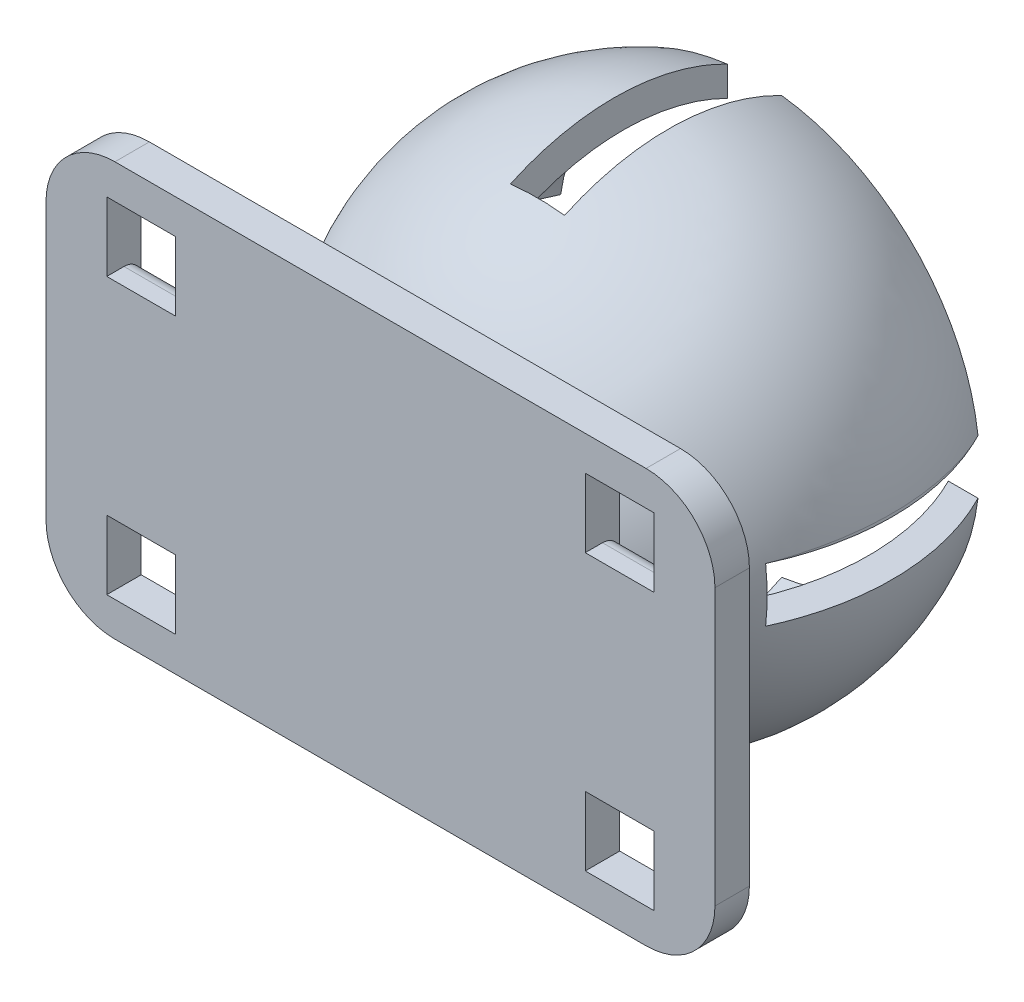
SolidWorks part; units mm, degrees
ref_plane "Front Plane" through (0, 0, 0) normal (0, 0, 1) x (1, 0, 0)
ref_plane "Top Plane" through (0, 0, 0) normal (0, 1, 0) x (1, 0, 0)
ref_plane "Right Plane" through (0, 0, 0) normal (1, 0, 0) x (0, 0, -1)
sketch "Sketch1" plane through (0, 0, 0) normal (0, 1, 0) x (1, 0, 0)
  line L0 (0, -22) -> (0, 22) construction
  line L1 (0, 22) -> (0, -22) construction
  line L3 (-16.302, 14.1421) -> (-19.0121, 14.1421) construction
  line L7 (0, -19.858) -> (0, -22)
  line L8 (-18.0365, 11.2951) -> (-20.7467, 11.2951)
  arc A4 (-19.0121, 14.1421) -> (0, -22) centre (-0.4092, 0.8563) ccw construction
  arc A6 (0, -19.858) -> (-20.0749, 4.7286) centre (1.3006, 1.6928) cw construction
  arc A9 (0, -19.858) -> (-18.0365, 11.2951) centre (1.3006, 1.6928) cw
  arc A10 (-20.7467, 11.2951) -> (0, -22) centre (-0.4092, 0.8563) ccw
  point P4 (0, 0)
  point P8 (0, 0)
  dimension "D1" = 44
  dimension "D2" = 21.59
  dimension "D3" = 22.86
  dimension "D4" = 36.1421
  dimension "D5" = 2.7102
  dimension "D6" = 21.59
revolve "Revolve2" add sketch "Sketch1" angle 360 about L0
sketch "Sketch2" plane through (0, 0, 0) normal (0, 1, 0) x (1, 0, 0)
  line L7 (20.7467, 11.2951) -> (-20.7467, 11.2951) construction
  line L16 (2.5, 11.2951) -> (-2.5, 11.2951)
  line L17 (2.5, 11.2951) -> (2.5, -8.7049)
  line L18 (2.5, -8.7049) -> (-2.5, -8.7049)
  line L19 (-2.5, 11.2951) -> (-2.5, -8.7049)
  point P4 (0, 11.2951)
  dimension "D1" = 5
  dimension "D2" = 20
sketch "Sketch3" plane through (0, 0, 0) normal (0, 0, 1) x (1, 0, 0)
  line L1 (-24.4729, -19.05) -> (24.4729, -19.05)
  line L2 (-30.8229, -12.7) -> (-30.8229, 12.7)
  line L3 (-24.4729, 19.05) -> (24.4729, 19.05)
  line L4 (30.8229, -12.7) -> (30.8229, 12.7)
  line L5 (-30.8229, -19.05) -> (30.8229, 19.05) construction
  line L6 (-30.8229, 19.05) -> (30.8229, -19.05) construction
  arc A0 (24.4729, 19.05) -> (30.8229, 12.7) centre (24.4729, 12.7) cw
  arc A1 (24.4729, -19.05) -> (30.8229, -12.7) centre (24.4729, -12.7) ccw
  arc A2 (-24.4729, -19.05) -> (-30.8229, -12.7) centre (-24.4729, -12.7) cw
  arc A3 (-30.8229, 12.7) -> (-24.4729, 19.05) centre (-24.4729, 12.7) cw
  point P0 (0, 0)
  dimension "D3" = 6.35
  dimension "D1" = 61.6458
  dimension "D2" = 38.1
extrude "Boss-Extrude1" add sketch "Sketch3" along normal blind 3.175 from offset 20
sketch "Sketch4" plane through (0, 0, 23.175) normal (0, 0, 1) x (1, 0, 0)
  line L0 (-30.8229, 0) -> (30.8229, 0) construction
  line L1 (-30.8229, 12.7) -> (-30.8229, -12.7) construction
  line L2 (30.8229, -12.7) -> (30.8229, 12.7) construction
  line L3 (0, -19.05) -> (0, 19.05) construction
  line L4 (-24.4729, -19.05) -> (24.4729, -19.05) construction
  line L5 (24.4729, 19.05) -> (-24.4729, 19.05) construction
  line L6 (-22.0472, -12.7) -> (-22.0472, 12.7) construction
  line L7 (25.2222, -9.525) -> (18.8722, -15.875) construction
  line L8 (-25.2222, 9.525) -> (-18.8722, 9.525)
  line L9 (-25.2222, 9.525) -> (-25.2222, 15.875)
  line L10 (-25.2222, 15.875) -> (-18.8722, 15.875)
  line L11 (-18.8722, 9.525) -> (-18.8722, 15.875)
  line L12 (-25.2222, 9.525) -> (-18.8722, 15.875) construction
  line L13 (-25.2222, 15.875) -> (-18.8722, 9.525) construction
  line L14 (-25.2222, -15.875) -> (-18.8722, -15.875)
  line L15 (-25.2222, -15.875) -> (-25.2222, -9.525)
  line L16 (-25.2222, -9.525) -> (-18.8722, -9.525)
  line L17 (-18.8722, -15.875) -> (-18.8722, -9.525)
  line L18 (-25.2222, -15.875) -> (-18.8722, -9.525) construction
  line L19 (-25.2222, -9.525) -> (-18.8722, -15.875) construction
  line L20 (25.2222, -15.875) -> (18.8722, -9.525) construction
  line L21 (25.2222, 15.875) -> (18.8722, 9.525) construction
  line L22 (25.2222, 9.525) -> (18.8722, 15.875) construction
  line L23 (22.0472, -12.7) -> (22.0472, 12.7) construction
  line L24 (18.8722, -15.875) -> (18.8722, -9.525)
  line L25 (25.2222, -9.525) -> (18.8722, -9.525)
  line L26 (25.2222, -15.875) -> (25.2222, -9.525)
  line L27 (25.2222, -15.875) -> (18.8722, -15.875)
  line L28 (18.8722, 9.525) -> (18.8722, 15.875)
  line L29 (25.2222, 15.875) -> (18.8722, 15.875)
  line L30 (25.2222, 9.525) -> (25.2222, 15.875)
  line L31 (25.2222, 9.525) -> (18.8722, 9.525)
  point P15 (-22.0472, 0)
  point P33 (22.0472, 0)
  dimension "D1" = 25.4
  dimension "D2" = 6.35
  dimension "D3" = 6.35
  dimension "D4" = 44.0944
extrude "Cut-Extrude4" cut sketch "Sketch4" against normal up to next
extrude "Cut-Extrude5" cut sketch "Sketch2" against normal blind 33.274
pattern_circular "CirPattern3" count 4 over 360 about axis through (0, 0, 0) along (0, 0, 1) of "Cut-Extrude5"
fillet "Fillet1" radius 1.5875 4 edges at (-22.0472, 9.525, 20) (-22.0472, -9.525, 20) (22.0472, -9.525, 20) (22.0472, 9.525, 20)
